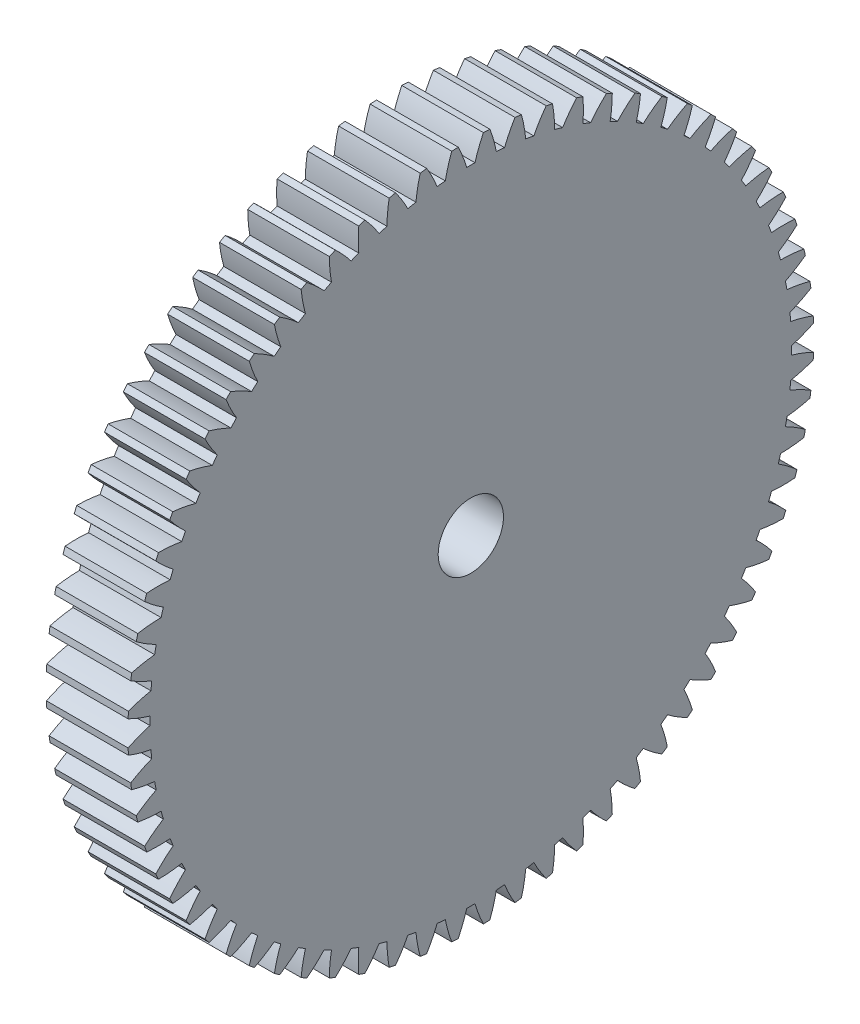
SolidWorks part; units mm, degrees
ref_plane "Plane1" through (0, 0, 0) normal (0, 0, 1) x (1, 0, 0)
ref_plane "Plane2" through (0, 0, 0) normal (0, 1, 0) x (1, 0, 0)
ref_plane "Plane3" through (0, 0, 0) normal (1, 0, 0) x (0, 0, -1)
sketch "HoldingSke" plane through (0, 0, 0) normal (0, 1, 0) x (1, 0, 0)
  line L0 (0, 0) -> (0.1249, -0.3091)
  line L1 (-15, 0) -> (100, 0) construction
  line L2 (0, 0) -> (-2.1039, 2.3779)
  line L3 (0, 0) -> (-11.863, 4.5341)
  line L4 (0, 0) -> (3.2351, 8.0072)
  line L5 (0, 0) -> (-46.8476, -17.4728)
  line L6 (0, 0) -> (-20.7241, -13.9826)
  line L7 (-2.1039, 2.3779) -> (8.6586, 51.2059)
  line L8 (-76.2, 54.61) -> (-73.4, 54.61)
  line L9 (-71.009, 38.7566) -> (-53.1078, 45.2721)
  line L10 (-76.2, 71.12) -> (104.1128, 71.12)
  line L11 (0, 0) -> (-25, 0)
  line L12 (-76.2, 101.6) -> (-76.093, 101.6)
  line L13 (24.9733, 27.94) -> (52.9518, 28.4284)
  line L14 (24.9733, 27.94) -> (24.9743, 27.94)
  line L15 (24.9733, 27.94) -> (100.4006, 29.5858)
  line L16 (-63.627, -3) -> (-12.827, -3)
  circle A0 centre (0, 0) radius 10
  circle A1 centre (0, 0) radius 37.5
  circle A2 centre (0, 0) radius 37.5
  circle A3 centre (0, 0) radius 10
  dimension "MHD" = 75
  dimension "Hub_dia" = 75
  dimension "Bore" = 20
  dimension "MBD" = 20
  dimension "Num_teeth" = 68
  dimension "Pitch" = 0.3333
  dimension "Overall_len" = 50
  dimension "Show_teeth" = 68
  dimension "Thickness" = 25
  dimension "OAL" = 50.0001
  dimension "T_dim" = 2.8
  dimension "Ap" = 20
  dimension "H" = 19.05
  dimension "Pitch_radius" = 180.3128
  dimension "Width" = 25
  dimension "Backlash" = 0.107
  dimension "Addendum_fac" = 1
  dimension "Dedendum_fac" = 1.25
  dimension "Clearance_fac" = 0.25
  dimension "Dedendum_add" = 0.001
  dimension "Module" = 3
sketch "BasProSke" plane through (0, 0, 0) normal (0, 1, 0) x (1, 0, 0)
  line L0 (-10, 0) -> (60, 0) construction
  line L1 (0, 0) -> (0, 105)
  line L2 (0, 0) -> (25, 0)
  line L3 (25, 0) -> (25, 105)
  line L4 (25, 105) -> (0, 105)
  dimension "Thickness" = 25
  dimension "Diameter" = 210
revolve "Base-Revolve" add sketch "BasProSke" angle 360 about L0
sketch "TooCutSke" plane through (0, 0, 0) normal (1, 0, 0) x (0, 0, -1)
  line L1 (0, 0) -> (0, 107) construction
  line L2 (0, 0) -> (-2.5432, 101.9683) construction
  line L3 (0, 0) -> (-9.4193, 203.7363) construction
  line L4 (-2.5432, 101.9683) -> (-4.7096, 101.8681) construction
  arc A0 (1.2658, 98.2408) -> (-1.2658, 98.2408) centre (0, 0) ccw
  arc A1 (3.8713, 104.954) -> (-3.8713, 104.954) centre (0, 0) ccw
  circle A2 centre (0, 0) radius 102 construction
  circle A3 centre (0, 0) radius 95.8486 construction
  arc A4 (-1.2658, 98.2408) -> (-3.8713, 104.954) centre (-40.4557, 86.8924) ccw
  arc A5 (3.8713, 104.954) -> (1.2658, 98.2408) centre (40.4557, 86.8924) ccw
  dimension "Root_dia" = 196.498
  dimension "Overcut_dia" = 210.0508
  dimension "Pitch_dia" = 204
  dimension "Base_dia" = 191.6973
  dimension "Flank_rad" = 40.8
  dimension "Half_ang" = 2.647
  dimension "Half_CT" = 2.1687
extrude "ToothCut" cut sketch "TooCutSke" along normal through all
fillet "Breaks" [suppressed] radius 0.06
fillet "RootFillets" [suppressed] radius 0.751
pattern_circular "TeethCuts" count 68 every 5.294 about axis through (-10, 0, 0) along (1, 0, 0) of "ToothCut", "RootFillets", "Breaks"
sketch "HubNeaOneSke" plane through (0, 0, 0) normal (-1, 0, 0) x (0, 0, 1)
  circle A0 centre (0, 0) radius 37.5
  dimension "Diameter" = 75
extrude "HubNearOne" [suppressed] add sketch "HubNeaOneSke" along normal blind 25.0001
sketch "HubNeaBotSke" plane through (0, 0, 0) normal (-1, 0, 0) x (0, 0, 1)
  circle A0 centre (0, 0) radius 37.5
  dimension "Diameter" = 75
extrude "HubNearBoth" [suppressed] add sketch "HubNeaBotSke" along normal blind 12.5
ref_plane "FarPln" through (25, 0, 0) normal (1, 0, 0) x (0, 0, -1)
sketch "HubFarSke" plane through (25, 0, 0) normal (1, 0, 0) x (0, 0, -1)
  circle A0 centre (0, 0) radius 37.5
  dimension "Diameter" = 75
extrude "HubFar" [suppressed] add sketch "HubFarSke" along normal blind 12.5
sketch "BorSke" plane through (0, 0, 0) normal (1, 0, 0) x (0, 0, -1)
  circle A0 centre (0, 0) radius 10
  dimension "Diameter" = 20
extrude "Bore" cut sketch "BorSke" along normal mid plane 100.0001
sketch "KeySke" plane through (0, 0, 0) normal (1, 0, 0) x (0, 0, -1)
  line L0 (-3, 0) -> (-3, 12.8)
  line L1 (-3, 12.8) -> (3, 12.8)
  line L2 (3, 12.8) -> (3, 0)
  line L3 (0, 0) -> (0, 34) construction
  line L4 (-3, 0) -> (3, 0)
  dimension "Offset" = 12.8
  dimension "Width" = 6
extrude "Keyway" [suppressed] cut sketch "KeySke" along normal mid plane 100.0001
pattern_circular "Keyway2" [suppressed] count 2 every 90 about axis through (-10, 0, 0) along (1, 0, 0)
equation "' \"Module@HoldingSke\" = 6.35"
equation "' \"Num_teeth@HoldingSke\" = 12"
equation "' \"Ap@HoldingSke\" =  20"
equation "' \"Ap@HoldingSke\" = 20"
equation "' \"Width@HoldingSke\" = 0.5 * 25.4"
equation "' \"Hub_dia@HoldingSke\"= 1 * 25.4"
equation "' \"Hub_dia@HoldingSke\" = 1 * 25.4"
equation "' \"Overall_len@HoldingSke\" = 1.0 * 25.4"
equation "' \"Bore@HoldingSke\" = 0.75 * 25.4"
equation "' \"T_dim@HoldingSke\" = 0.1 * 25.4"
equation "' \"Width@KeySke\" = 0.25 * 25.4"
equation "' \"Show_teeth@HoldingSke\" = 13"
equation "' \"Backlash@HoldingSke\" = 0.009 * 25.4"
equation "' \"Addendum_fac@HoldingSke\" = 1.0"
equation "' \"Dedendum_fac@HoldingSke\" = 1.25"
equation "' \"Dedendum_add@HoldingSke\" = 0.00005 * 25.4"
equation "' \"Clearance_fac@HoldingSke\" = 0.25"
equation "\"Pitch@HoldingSke\" = 1 / \"Module@HoldingSke\""
equation "\"Overcut_dia@TooCutSke\" = (\"Num_teeth@HoldingSke\" + 2 * \"Addendum_fac@HoldingSke\") / \"Pitch@HoldingSke\" + 0.002 * 25.4"
equation "\"Pitch_dia@TooCutSke\" = \"Num_teeth@HoldingSke\" / \"Pitch@HoldingSke\""
equation "\"Base_dia@TooCutSke\" = \"Num_teeth@HoldingSke\" / \"Pitch@HoldingSke\" * cos((\"Ap@HoldingSke\"  * 3.14159265 / 180))"
equation "\"Root_dia@TooCutSke\" = (\"Num_teeth@HoldingSke\" + 2) / \"Pitch@HoldingSke\" - 2 * (\"Addendum_fac@HoldingSke\" + \"Dedendum_fac@HoldingSke\") / \"Pitch@HoldingSke\" - \"Dedendum_add@HoldingSke\" * 2"
equation "\"Half_ang@TooCutSke\" = 180 / \"Num_teeth@HoldingSke\""
equation "\"Half_CT@TooCutSke\" = \"Num_teeth@HoldingSke\" / \"Pitch@HoldingSke\" * sin((3.14159265 / 2 / \"Num_teeth@HoldingSke\")) / 2 - 7 * \"Backlash@HoldingSke\" / 4"
equation "\"Flank_rad@TooCutSke\" = \"Num_teeth@HoldingSke\" / \"Pitch@HoldingSke\" / 5"
equation "\"Radius@RootFillets\" = \"Clearance_fac@HoldingSke\" / \"Pitch@HoldingSke\" + \"Dedendum_add@HoldingSke\""
equation "\"Break_rad@Breaks\" = 0.02 / \"Pitch@HoldingSke\""
equation "\"Thickness@HoldingSke\" = \"Width@HoldingSke\""
equation "\"OAL@HoldingSke\" = \"Thickness@HoldingSke\""
equation "\"MHD@HoldingSke\" = (\"Num_teeth@HoldingSke\" + 2) / \"Pitch@HoldingSke\" - 2 * (\"Addendum_fac@HoldingSke\" + \"Dedendum_fac@HoldingSke\")  / \"Pitch@HoldingSke\" - \"Dedendum_add@HoldingSke\" * 2"
equation "\"MBD@HoldingSke\" = (\"Num_teeth@HoldingSke\" + 2) / \"Pitch@HoldingSke\" - 2 * (\"Addendum_fac@HoldingSke\" + \"Dedendum_fac@HoldingSke\")  / \"Pitch@HoldingSke\" - \"Dedendum_add@HoldingSke\" * 2 - 0.002 * 25.4"
equation "\"MHD@HoldingSke\" = ((sgn( \"MHD@HoldingSke\" - \"Hub_dia@HoldingSke\" )-1)*( \"MHD@HoldingSke\" - \"Hub_dia@HoldingSke\" ))/-2+ \"Hub_dia@HoldingSke\""
equation "\"MBD@HoldingSke\" = ((sgn( \"MBD@HoldingSke\" - \"Bore@HoldingSke\" )-1)*( \"MBD@HoldingSke\" - \"Bore@HoldingSke\" ))/-2+ \"Bore@HoldingSke\""
equation "\"OAL@HoldingSke\" = ((sgn( \"OAL@HoldingSke\" - \"Overall_len@HoldingSke\" )+1)*( \"OAL@HoldingSke\" - \"Overall_len@HoldingSke\" ))/2 + \"Overall_len@HoldingSke\" + 0.000002 * 25.4"
equation "\"Num_teeth@TeethCuts\" = int( \"Show_teeth@HoldingSke\" ) + 1"
equation "\"Num_teeth@TeethCuts\" = ((sgn( \"Num_teeth@TeethCuts\" - \"Num_teeth@HoldingSke\" )-1)*( \"Num_teeth@TeethCuts\" - \"Num_teeth@HoldingSke\" ))/-2+ \"Num_teeth@HoldingSke\""
equation "\"Num_teeth@TeethCuts\" = ((sgn( \"Num_teeth@TeethCuts\" - 2.0)+1)*( \"Num_teeth@TeethCuts\" - 2.0))/2 +2.0"
equation "\"Angle@TeethCuts\" = 360.0 / \"Num_teeth@HoldingSke\""
equation "\"Diameter@BasProSke\" = (\"Num_teeth@HoldingSke\" + 2 * \"Addendum_fac@HoldingSke\") / \"Pitch@HoldingSke\""
equation "\"Thickness@BasProSke\"  = \"Thickness@HoldingSke\""
equation "' \"Fillet_rad@BasProSke\" =  \"Thickness@HoldingSke\" * 0.05"
equation "' \"Fillet_rad@BasProSke\" = \"Thickness@HoldingSke\" * 0.05"
equation "\"MHD@HoldingSke\" = ((sgn( \"MHD@HoldingSke\" - \"Root_dia@TooCutSke\" )-1)*( \"MHD@HoldingSke\" - \"Root_dia@TooCutSke\" ))/-2+ \"Root_dia@TooCutSke\""
equation "\"Diameter@HubNeaOneSke\" = \"MHD@HoldingSke\""
equation "\"Length@HubNearOne\" = \"OAL@HoldingSke\" - \"Thickness@BasProSke\""
equation "\"Diameter@HubNeaBotSke\" = \"MHD@HoldingSke\""
equation "\"Length@HubNearBoth\" = ( \"OAL@HoldingSke\" - \"Thickness@BasProSke\" ) / 2.0"
equation "\"Thickness@FarPln\" = \"Thickness@BasProSke\""
equation "\"Diameter@HubFarSke\" = \"MHD@HoldingSke\""
equation "\"Length@HubFar\" = ( \"OAL@HoldingSke\" - \"Thickness@BasProSke\" ) / 2.0"
equation "\"Diameter@BorSke\" = \"MBD@HoldingSke\""
equation "\"D1@Bore\" = \"OAL@HoldingSke\" * 2.0"
equation "\"D1@Keyway\" = \"OAL@HoldingSke\" * 2.0"
equation "\"Offset@KeySke\" = \"T_dim@HoldingSke\" + \"MBD@HoldingSke\" / 2.0"
